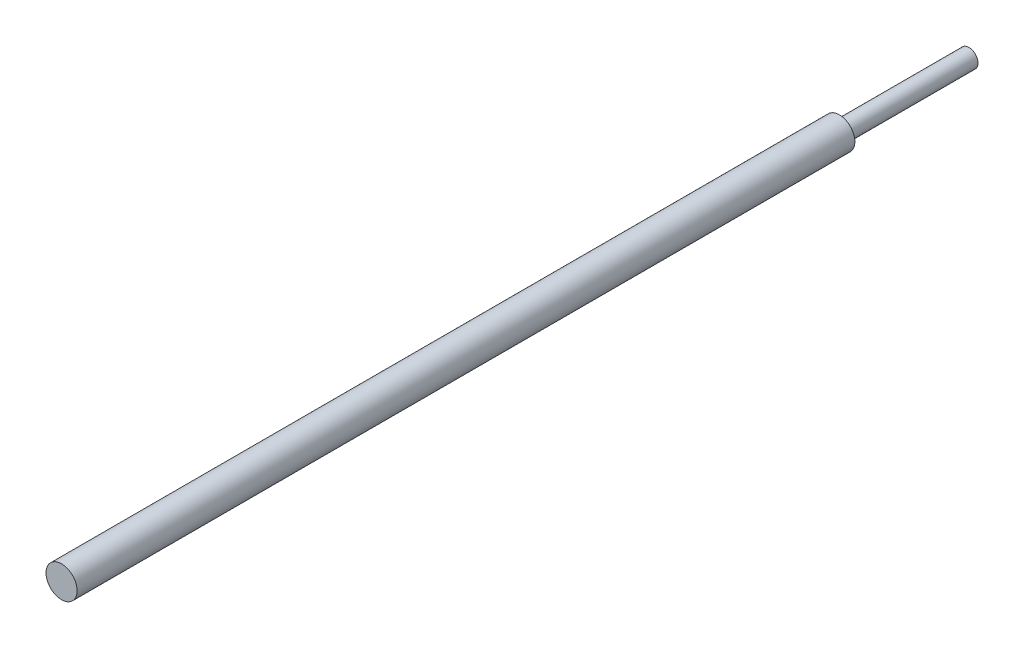
SolidWorks part; units mm, degrees
ref_plane "Спереди" through (0, 0, 0) normal (0, 0, 1) x (1, 0, 0)
ref_plane "Сверху" through (0, 0, 0) normal (0, 1, 0) x (1, 0, 0)
ref_plane "Справа" through (0, 0, 0) normal (1, 0, 0) x (0, 0, -1)
sketch "Эскиз1" plane through (0, 0, 0) normal (0, 0, 1) x (1, 0, 0)
  circle A0 centre (0, 0) radius 0.35
  dimension "D1" = 0.7
extrude "Вытянуть1" add sketch "Эскиз1" along normal blind 5
sketch "Эскиз2" plane through (0, 0, 5) normal (0, 0, 1) x (1, 0, 0)
  circle A0 centre (0, 0) radius 0.6
  dimension "D1" = 1.2
extrude "Вытянуть2" add sketch "Эскиз2" along normal blind 30
